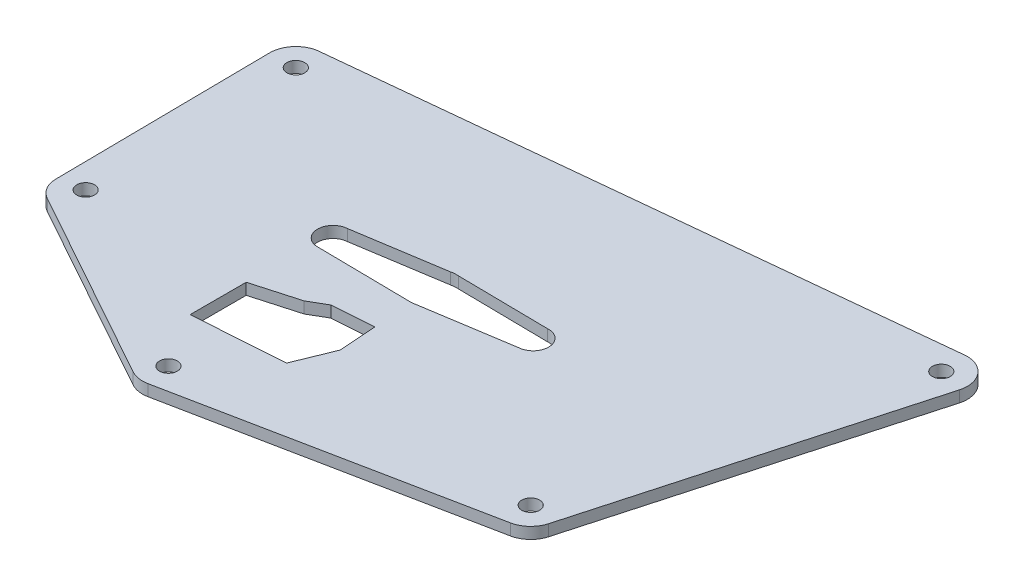
SolidWorks part; units mm, degrees
ref_plane "Front Plane" through (0, 0, 0) normal (0, 0, 1) x (1, 0, 0)
ref_plane "Top Plane" through (0, 0, 0) normal (0, 1, 0) x (1, 0, 0)
ref_plane "Right Plane" through (0, 0, 0) normal (1, 0, 0) x (0, 0, -1)
sketch "Sketch2" plane through (0, 0, 0) normal (0, 1, 0) x (1, 0, 0)
  line L0 (602.2882, -78.7714) -> (811.0416, 604.0302) construction
sketch "Sketch1" plane through (0, 0, 0) normal (0, 1, 0) x (1, 0, 0)
  line L0 (-6.823, -7.4882) -> (47.147, -37.4723)
  line L1 (0.8879, 1.746) -> (0.8879, 1.9982) construction
  line L2 (52.0977, -38.2428) -> (136.3593, -21.3082)
  line L3 (141.9163, -16.1444) -> (166.9034, 73.5687)
  line L4 (-4.3661, 66.0537) -> (159.1821, 82.7288)
  line L5 (-10.9695, 58.6673) -> (-10.2889, -1.673)
  line L6 (0.8879, 57.4592) -> (0.8879, 57.626) construction
  arc A1 (-1.7855, 60.3977) -> (-2.8, 56.5177) centre (0.8879, 57.626) ccw construction
  circle A3 centre (159.9176, 75.5145) radius 2.4892
  circle A4 centre (134.9305, -14.1987) radius 2.4892
  circle A5 centre (50.6688, -31.1332) radius 2.4892
  arc A7 (-10.2889, -1.673) -> (-6.823, -7.4882) centre (-3.55, -1.597) ccw
  arc A8 (47.147, -37.4723) -> (52.0977, -38.2428) centre (50.6688, -31.1332) ccw
  arc A9 (136.3593, -21.3082) -> (141.9163, -16.1444) centre (134.9305, -14.1987) ccw
  arc A10 (166.9034, 73.5687) -> (159.1821, 82.7288) centre (159.9176, 75.5145) ccw
  arc A11 (-4.3661, 66.0537) -> (-10.9695, 58.6673) centre (-3.7196, 58.8308) ccw
  circle A12 centre (-3.7196, 58.8308) radius 2.4892
  circle A13 centre (50.6688, -31.1332) radius 7.2517 construction
  circle A14 centre (134.9305, -14.1987) radius 7.2517 construction
  circle A15 centre (159.9176, 75.5145) radius 7.2517 construction
  circle A16 centre (-3.5081, -0.086) radius 2.4892
  circle A17 centre (-3.7196, 58.8308) radius 7.2517 construction
  dimension "D2" = 160.0326
  dimension "D3" = 4.7625
  dimension "D7" = 4.7625
  dimension "D6" = 4.9784
  dimension "D1" = 4.7625
  dimension "D4" = 152.073
  dimension "D5" = 101.7661
  dimension "D9" = 4.7625
extrude "Boss-Extrude1" add sketch "Sketch1" along normal blind 3.175
sketch "Sketch3" plane through (0, 3.175, 0) normal (0, 1, 0) x (1, 0, 0)
  line L0 (41.2559, -15.6784) -> (66.4681, -13.884)
  line L1 (66.4681, -13.884) -> (70.7748, -3.2967)
  line L2 (70.7748, -3.2967) -> (70.0328, 7.1286)
  line L3 (70.0328, 7.1286) -> (58.5655, 6.3125)
  line L4 (58.5655, 6.3125) -> (53.862, 3.5831)
  line L5 (53.862, 3.5831) -> (41.2559, 0)
  line L6 (41.2559, 0) -> (41.2559, -15.6784)
extrude "trigger cutout" cut sketch "Sketch3" against normal blind 3.175
sketch "Sketch4" plane through (0, 3.175, 0) normal (0, 1, 0) x (1, 0, 0)
  line L0 (70.7748, -3.2967) -> (70.0328, 7.1286) construction
  line L16 (68.7831, 24.6864) -> (94.8791, 26.5438) construction
  line L17 (94.7226, 28.7427) -> (93.6572, 43.7111) construction
  line L18 (69.4259, 31.1952) -> (94.5726, 30.8509)
  line L19 (70.3413, 18.3342) -> (95.1857, 22.2367)
  line L20 (42.5306, 25.028) -> (41.9077, 33.7808) construction
  line L21 (42.9937, 18.5219) -> (68.1403, 18.1776)
  line L22 (42.3806, 27.1361) -> (67.2249, 31.0386)
  arc A0 (68.1403, 18.1776) -> (70.3413, 18.3342) centre (68.7831, 24.6864) ccw
  arc A1 (95.1857, 22.2367) -> (94.5726, 30.8509) centre (94.8791, 26.5438) ccw
  arc A2 (42.3806, 27.1361) -> (42.9937, 18.5219) centre (42.6871, 22.829) ccw
  arc A3 (69.4259, 31.1952) -> (67.2249, 31.0386) centre (68.7831, 24.6864) ccw
  point P4 (0, 0)
  point P7 (68.8667, 23.5129)
  point P9 (94.5726, 30.8509)
  point P10 (0, 0)
  point P15 (69.4227, 24.7319)
  dimension "D1" = 13.081
  dimension "D2" = 8.636
  dimension "D3" = 26.162
  dimension "D4" = 26.162
extrude "servo cutout" cut sketch "Sketch4" against normal blind 3.175
